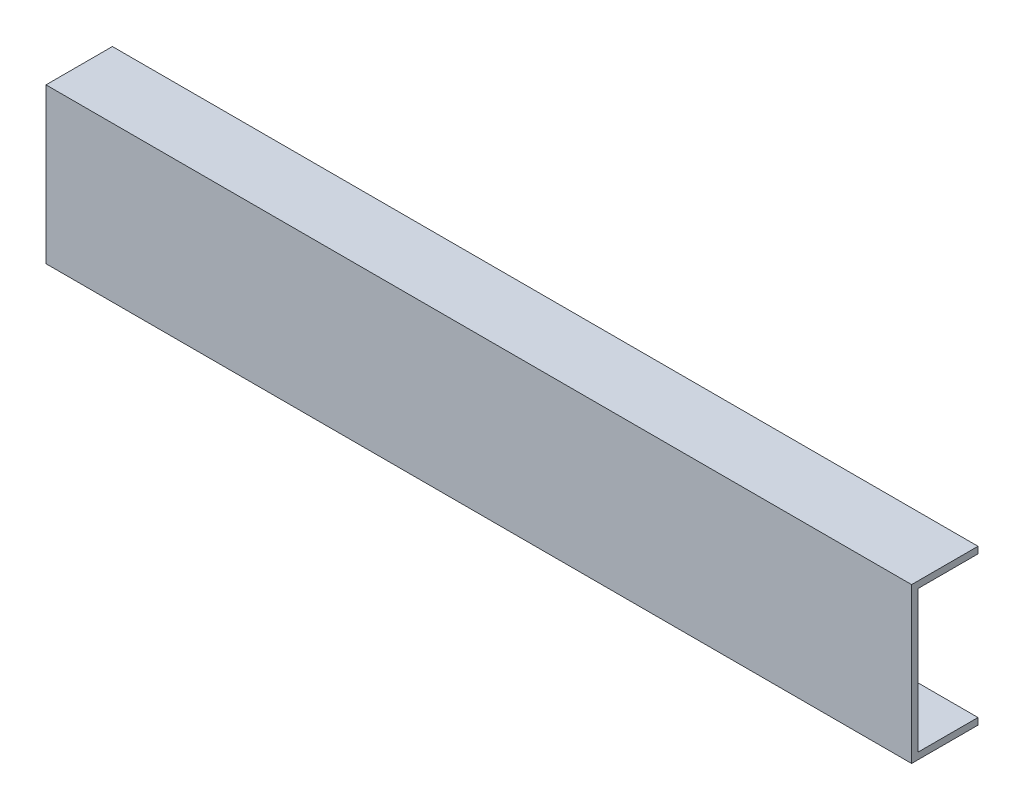
SolidWorks part; units mm, degrees
ref_plane "Plano frontal" through (0, 0, 0) normal (0, 0, 1) x (1, 0, 0)
ref_plane "Plano superior" through (0, 0, 0) normal (0, 1, 0) x (1, 0, 0)
ref_plane "Plano direito" through (0, 0, 0) normal (1, 0, 0) x (0, 0, -1)
sketch "Esboço1" plane through (0, 0, 0) normal (1, 0, 0) x (0, 0, -1)
  line L0 (0, 0) -> (-30, 0)
  line L1 (-30, 0) -> (-30, 70)
  line L2 (-30, 70) -> (0, 70)
  line L3 (0, 3) -> (-27, 3)
  line L4 (-27, 3) -> (-27, 67)
  line L5 (-27, 67) -> (0, 67)
  line L6 (0, 70) -> (0, 67)
  line L7 (0, 3) -> (0, 0)
  dimension "D1" = 70
  dimension "D2" = 30
  dimension "D3" = 30
  dimension "D4" = 3
extrude "Ressalto-extrusão1" add sketch "Esboço1" along normal blind 391.08
